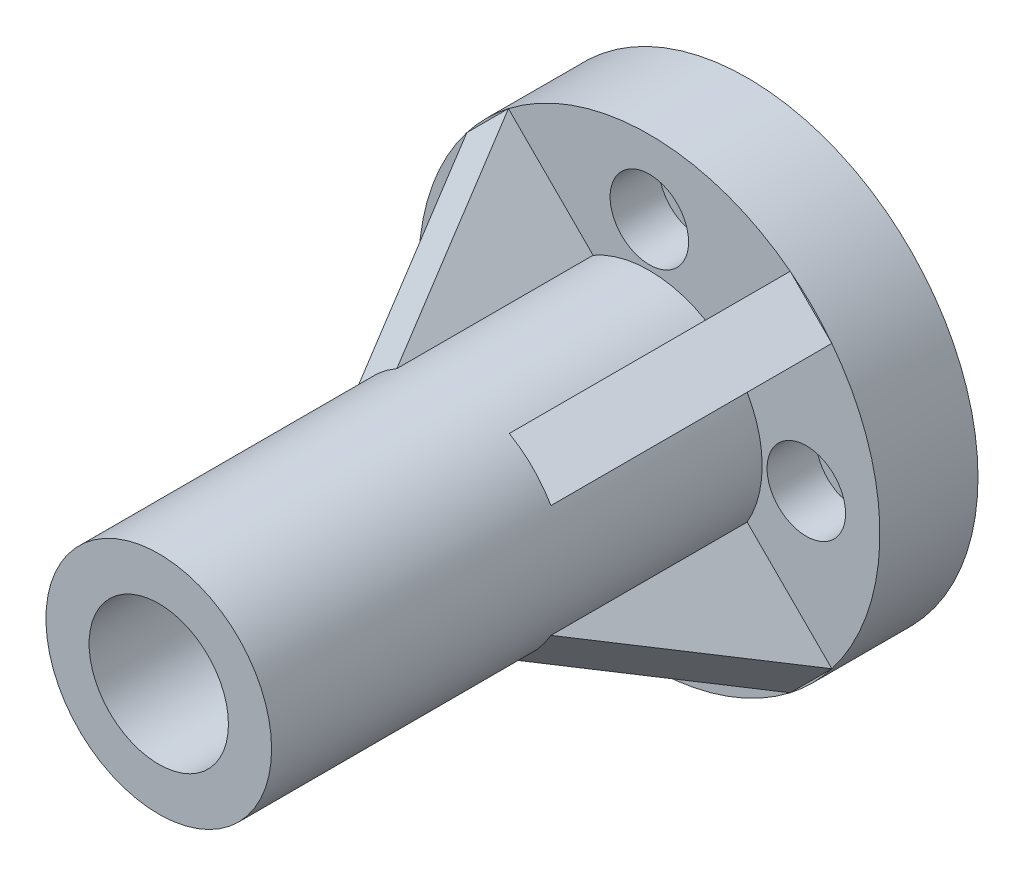
SolidWorks part; units mm, degrees
material "TPU"
ref_plane "Alzado" through (0, 0, 0) normal (0, 0, 1) x (1, 0, 0)
ref_plane "Planta" through (0, 0, 0) normal (0, 1, 0) x (1, 0, 0)
ref_plane "Vista lateral" through (0, 0, 0) normal (1, 0, 0) x (0, 0, -1)
sketch "Croquis1" plane through (0, 0, 0) normal (0, 0, 1) x (1, 0, 0)
  circle A0 centre (0, 0) radius 11.75
  dimension "D1" = 23.5
extrude "Saliente-Extruir1" add sketch "Croquis1" along normal blind 5
sketch "Croquis2" plane through (0, 0, 5) normal (0, 0, 1) x (1, 0, 0)
  line L0 (0, 9.538) -> (0, -9.5091) construction
  line L1 (-9.7262, 0) -> (9.3788, 0) construction
  circle A0 centre (0, 0) radius 8
  dimension "D1" = 16
hole_wizard "Refrentado para tornillo con cabeza plana de M21" positions "Croquis3D1" profile "Croquis3" counterbore size "M2" standard "ISO" end condition through all
sketch3d "Croquis3D1"
  line L0 (0, 9.538, 5) -> (0, -9.5091, 5) construction
  line L1 (-9.7262, 0, 5) -> (9.3788, 0, 5) construction
  circle A0 centre (0, 0, 5) radius 8 construction
  point P0 (0, 8, 5)
  point P4 (0, 0, 13)
  point P7 (8, 0.0145, 5)
  point P9 (0, -8, 5)
  point P11 (-8, 0, 5)
sketch "Croquis3" plane through (0, 8, 5) normal (1, 0, 0) x (0, -1, 0)
  line L0 (0, 0) -> (0, 5)
  line L1 (0, 5) -> (1, 5)
  line L3 (1, 5) -> (1, 2.5)
  line L4 (1, 2.5) -> (2, 2.5)
  line L5 (2, 2.5) -> (2, 0)
  line L7 (2, 0) -> (0, 0)
  line L11 (0, -6.35) -> (0, 107.95) construction
  dimension "Diámetro de taladro hasta el siguiente" = 2
  dimension "Profundidad de taladro hasta el siguiente" = 5
  dimension "Diámetro de refrentado" = 4
  dimension "Profundidad de refrentado" = 2.5
sketch "Croquis6" plane through (0, 0, 0) normal (0, 0, -1) x (-1, 0, 0)
  line L0 (0, 9.538) -> (0, -9.5091) construction
  circle A0 centre (0, 0.0145) radius 4.25
  dimension "D1" = 8.5
extrude "Cortar-Extruir1" cut sketch "Croquis6" against normal blind 1.9
sketch "Croquis7" plane through (0, 0, 5) normal (0, 0, 1) x (1, 0, 0)
  circle A0 centre (0, 0) radius 5.75
  dimension "D1" = 11.5
extrude "Saliente-Extruir2" add sketch "Croquis7" along normal blind 15
sketch "Croquis8" plane through (0, 0, 20) normal (0, 0, 1) x (1, 0, 0)
  circle A0 centre (0, 0) radius 5.75
  dimension "D1" = 11.5
extrude "Saliente-Extruir3" add sketch "Croquis8" along normal blind 10
sketch "Croquis9" plane through (0, 0, 30) normal (0, 0, 1) x (1, 0, 0)
  circle A0 centre (0, 0) radius 3.55
  dimension "D1" = 7.1
extrude "Cortar-Extruir2" cut sketch "Croquis9" against normal blind 20
sketch "Croquis10" plane through (0, 0, 5) normal (0, 0, 1) x (1, 0, 0)
  line L0 (0, 0) -> (-8.3085, 8.3085) construction
  line L1 (-8.3085, 8.3085) -> (-4.0659, 4.0659) construction
  line L2 (-6.2822, 6.2822) -> (-7.3429, 5.2216) construction
  line L3 (-7.3429, 5.2216) -> (-5.2216, 7.3429) construction
  line L4 (-7.3429, 5.2216) -> (-9.3012, 7.1799)
  line L5 (-7.3429, 5.2216) -> (-4.9857, 2.8644)
  line L6 (-5.2216, 7.3429) -> (-2.8644, 4.9857)
  line L7 (-5.2216, 7.3429) -> (-7.1799, 9.3012)
  circle A0 centre (0, 0) radius 5.75 construction
  circle A1 centre (0, 0) radius 11.75
  arc A2 (-7.1799, 9.3012) -> (-9.3012, 7.1799) centre (0, 0) ccw
  arc A3 (-2.8644, 4.9857) -> (-4.9857, 2.8644) centre (0, 0) ccw
  dimension "D2" = 1.5
  dimension "D3" = 3
  dimension "D1" = 0
extrude "Saliente-Extruir4" add sketch "Croquis10" along normal blind 10
sketch "Croquis11" plane through (-1.0607, -1.0607, 0) normal (-0.7071, -0.7071, 0) x (0, 0, 1)
  line L1 (15, 5.5509) -> (15, 11.7842)
  line L2 (15, 11.6539) -> (15, 5.5509) construction
  line L5 (5, 11.7807) -> (15, 11.7842)
  line L6 (15, 5.5509) -> (5, 11.6539)
  line L7 (5, 11.6539) -> (5, 11.7807)
extrude "Cortar-Extruir3" cut sketch "Croquis11" against normal blind 3
pattern_circular "MatrizC1" count 4 over 360 about axis through (0, 0, 0) along (0, 0, 1) of "Saliente-Extruir4", "Cortar-Extruir3"
